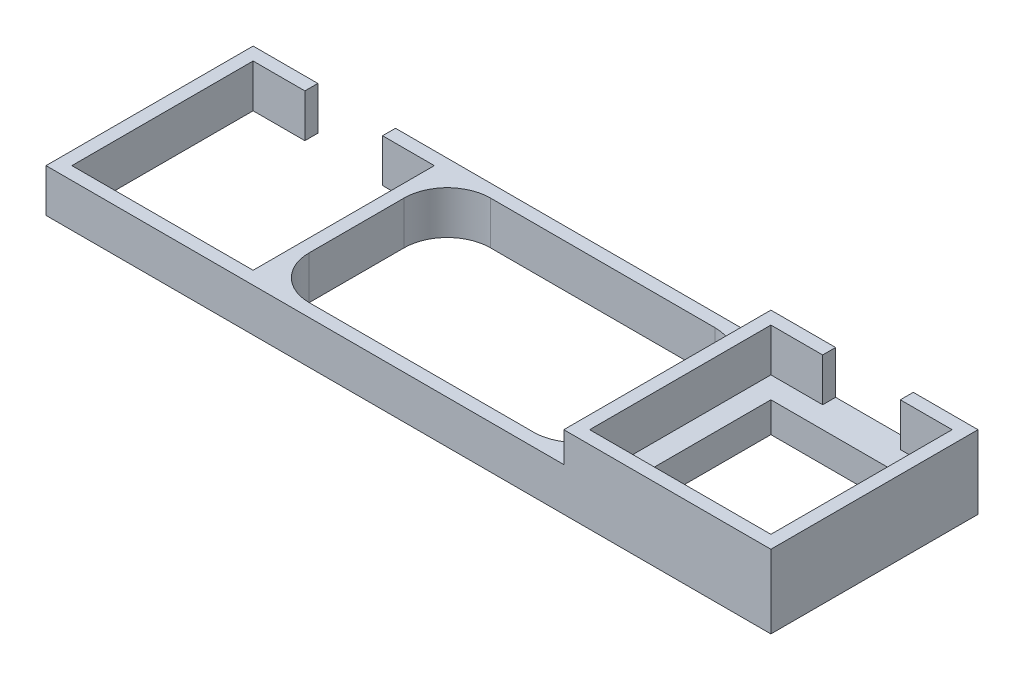
SolidWorks part; units mm, degrees
ref_plane "Front Plane" through (0, 0, 0) normal (0, 0, 1) x (1, 0, 0)
ref_plane "Top Plane" through (0, 0, 0) normal (0, 1, 0) x (1, 0, 0)
ref_plane "Right Plane" through (0, 0, 0) normal (1, 0, 0) x (0, 0, -1)
sketch "Sketch1" plane through (0, 0, 0) normal (0, 1, 0) x (1, 0, 0)
  line L1 (-162, 42) -> (-120, 42)
  line L2 (-162, 42) -> (-162, 0)
  line L3 (-162, 0) -> (-120, 0)
  line L4 (-120, 42) -> (-120, 0)
  line L5 (-42, 42) -> (0, 42)
  line L6 (-42, 42) -> (-42, 0)
  line L7 (-42, 0) -> (0, 0)
  line L8 (0, 42) -> (0, 0)
  line L9 (-165, 45) -> (3, 45)
  line L10 (-165, 45) -> (-165, -3)
  line L11 (-165, -3) -> (3, -3)
  line L12 (3, 45) -> (3, -3)
  line L13 (-117, 42) -> (-45, 42)
  line L14 (-117, 42) -> (-117, 0)
  line L15 (-117, 0) -> (-45, 0)
  line L16 (-45, 42) -> (-45, 0)
  point P8 (-21, 0)
  point P10 (-141, 0)
  dimension "D1" = 42
  dimension "D2" = 42
  dimension "D3" = 42
  dimension "D4" = 120
  dimension "D5" = 3
  dimension "D6" = 3
  dimension "D7" = 3
  dimension "D8" = 3
  dimension "D9" = 3
  dimension "D10" = 3
  dimension "D11" = 3
  dimension "D12" = 3
extrude "Boss-Extrude1" add sketch "Sketch1" along normal blind 10 contours L4 L3 L2 L1
sketch "Sketch2" plane through (0, 0, -45) normal (0, 0, -1) x (-1, 0, 0)
  line L0 (-3, 10) -> (165, 10) construction
  line L1 (12, 10) -> (30, 10)
  line L2 (12, 10) -> (12, 0)
  line L3 (12, 0) -> (30, 0)
  line L4 (30, 10) -> (30, 0)
  line L5 (-3, 0) -> (165, 0) construction
  line L6 (0, 10) -> (0, 0) construction
  line L7 (132, 10) -> (150, 10)
  line L8 (132, 10) -> (132, 0)
  line L9 (132, 0) -> (150, 0)
  line L10 (150, 10) -> (150, 0)
  line L12 (120, 10) -> (120, 0) construction
  dimension "D1" = 18
  dimension "D2" = 18
  dimension "D3" = 12
  dimension "D4" = 12
extrude "Cut-Extrude1" cut sketch "Sketch2" against normal blind 10
sketch "Sketch3" plane through (0, 0, 0) normal (0, -1, 0) x (1, 0, 0)
  line L1 (-37, -5) -> (-5, -5)
  line L2 (-37, -5) -> (-37, -37)
  line L3 (-37, -37) -> (-5, -37)
  line L4 (-5, -5) -> (-5, -37)
  line L5 (-42, 0) -> (0, 0)
  line L6 (-42, 0) -> (-42, -42)
  line L7 (-42, -42) -> (0, -42)
  line L8 (0, 0) -> (0, -42)
  dimension "D1" = 5
  dimension "D2" = 5
  dimension "D3" = 5
  dimension "D4" = 5
extrude "Boss-Extrude2" add sketch "Sketch3" against normal blind 7
sketch "Sketch4" plane through (0, 10, 0) normal (0, 1, 0) x (1, 0, 0)
  line L0 (-30, 45) -> (-132, 45) construction
  line L1 (-30, 42) -> (-42, 42)
  line L2 (-30, 42) -> (-30, 45)
  line L3 (-30, 45) -> (-45, 45)
  line L4 (-45, 42) -> (-45, 45)
  line L5 (-165, -3) -> (3, -3) construction
  line L6 (-45, -3) -> (-42, -3)
  line L7 (-45, -3) -> (-45, 45)
  line L8 (-45, 45) -> (-42, 45)
  line L9 (-42, 0) -> (-42, 42)
  line L10 (3, -3) -> (3, 45) construction
  line L11 (-45, -3) -> (3, -3)
  line L12 (-45, -3) -> (-45, 0)
  line L13 (-42, 0) -> (0, 0)
  line L14 (3, -3) -> (3, 0)
  line L15 (-42, 42) -> (-42, 0) construction
  line L17 (3, 0) -> (3, 45)
  line L18 (3, 45) -> (0, 45)
  line L19 (0, 0) -> (0, 42)
  line L20 (-12, 45) -> (3, 45)
  line L21 (-12, 45) -> (-12, 42)
  line L22 (-12, 42) -> (0, 42)
  line L23 (3, 45) -> (3, 42)
  line L24 (-45, 0) -> (-45, 42) construction
  line L25 (0, 42) -> (0, 0) construction
  line L26 (-12, 42) -> (0, 42) construction
  line L27 (-42, 0) -> (0, 0) construction
  line M21 (-12, 45) -> (-12, 42)
  line M22 (-12, 42) -> (0, 42)
  line M23 (0, 42) -> (0, 0)
  line M24 (0, 0) -> (-42, 0)
  line M25 (-42, 0) -> (-42, 42)
  line M26 (-42, 42) -> (-30, 42)
  line M27 (-30, 42) -> (-30, 45)
  line M28 (-30, 45) -> (-132, 45)
  line M38 (-165, -3) -> (3, -3)
  line M39 (3, -3) -> (3, 45)
  line M40 (3, 45) -> (-12, 45)
  line M44 (-45, 42) -> (-45, 0)
extrude "Boss-Extrude3" add sketch "Sketch4" along normal blind 7 contours L7 L17 L3 L4 M38 M39 M40 M21 M22 M23 M24 M25 M26 M27 M28 M44
fillet "Fillet1" radius 10 4 edges at (-45, 5, -42) (-117, 5, -42) (-45, 5, 0) (-117, 5, 0)
sketch "Sketch6" plane through (0, 0, -42) normal (0, 0, -1) x (-1, 0, 0)
  line L0 (12, 17) -> (12, 0) construction
  line L1 (12, 7) -> (30, 7)
  line L2 (12, 7) -> (12, 0)
  line L3 (12, 0) -> (30, 0)
  line L4 (30, 7) -> (30, 0)
  line L5 (12, 0) -> (12, 7) construction
  line L6 (30, 7) -> (12, 7) construction
extrude "Boss-Extrude4" add sketch "Sketch6" along normal up to surface (3 mm away) up to face at (-69, 9, -45)
